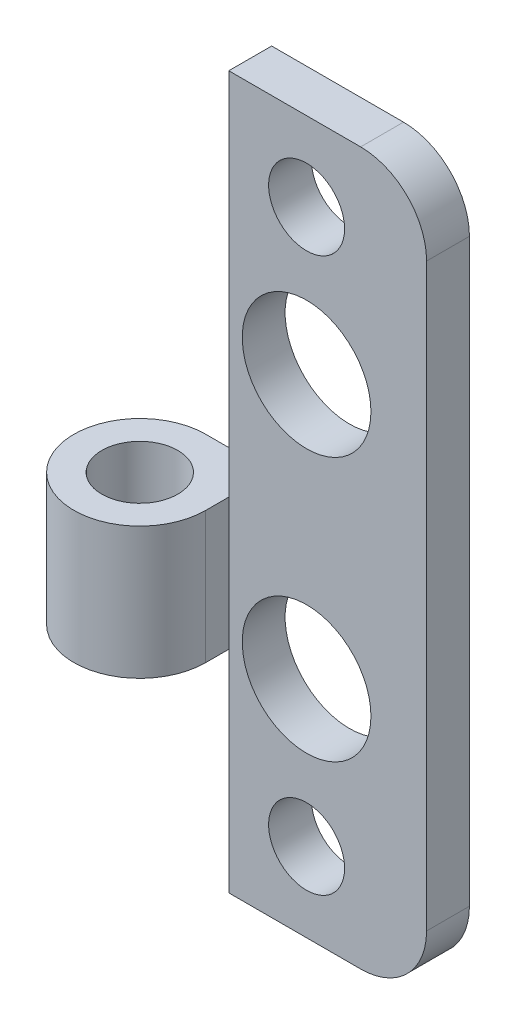
SolidWorks part; units mm, degrees
ref_plane "Front Plane" through (0, 0, 0) normal (0, 0, 1) x (1, 0, 0)
ref_plane "Top Plane" through (0, 0, 0) normal (0, 1, 0) x (1, 0, 0)
ref_plane "Right Plane" through (0, 0, 0) normal (1, 0, 0) x (0, 0, -1)
sketch "Sketch1" plane through (0, 0, 0) normal (0, 0, 1) x (1, 0, 0)
  line L0 (7.493, 46.99) -> (7.493, 54.61) construction
  line L1 (0, 0) -> (12.7, 0)
  line L2 (0, 0) -> (0, 68.58)
  line L3 (0, 68.58) -> (12.7, 68.58)
  line L4 (19.05, 6.35) -> (19.05, 62.23)
  line L5 (7.493, 46.99) -> (7.493, 21.59) construction
  line L6 (7.493, 34.29) -> (0, 34.29) construction
  circle A0 centre (7.493, 46.99) radius 3.6576 construction
  circle A1 centre (7.493, 21.59) radius 3.6576 construction
  circle A2 centre (7.493, 60.96) radius 3.6576
  circle A3 centre (7.493, 7.62) radius 3.6576
  arc A4 (12.7, 0) -> (19.05, 6.35) centre (12.7, 6.35) ccw
  arc A5 (19.05, 62.23) -> (12.7, 68.58) centre (12.7, 62.23) ccw
  circle A6 centre (7.493, 46.99) radius 6.1976 construction
  circle A7 centre (7.493, 21.59) radius 6.1976 construction
  circle A8 centre (7.493, 60.96) radius 6.1976 construction
  circle A9 centre (7.493, 7.62) radius 6.1976 construction
  point P16 (19.05, 0)
  dimension "D4" = 7.493
  dimension "D6" = 6.35
  dimension "D7" = 7.3152
  dimension "D9" = 7.62
  dimension "D1" = 19.05
  dimension "D2" = 68.58
  dimension "D3" = 7.62
  dimension "D5" = 25.4
  dimension "D8" = 7.62
extrude "Boss-Extrude1" add sketch "Sketch1" along normal blind 4.1275
sketch "Sketch2" plane through (0, 68.58, 0) normal (0, 1, 0) x (1, 0, 0)
  line L0 (0, 0) -> (-6.35, 0)
  line L2 (0, -6.35) -> (0, -4.1275)
  line L3 (0, -4.1275) -> (0, 0)
  circle A0 centre (-6.35, -6.35) radius 3.6576
  arc A2 (-6.35, 0) -> (0, -6.35) centre (-6.35, -6.35) ccw
  point P6 (-20.32, 0)
  dimension "D2" = 7.3152
  dimension "D1" = 6.35
extrude "Boss-Extrude2" add sketch "Sketch2" against normal blind 12.7 from offset 35.56 offset against normal yes
sketch "Sketch3" plane through (0, 0, 4.1275) normal (0, 0, 1) x (1, 0, 0)
  line L0 (0, 20.32) -> (0, 0) construction
  line L1 (7.493, 46.99) -> (7.493, 21.59) construction
  line L2 (7.493, 34.29) -> (19.05, 34.29) construction
  line L3 (19.05, 6.35) -> (19.05, 62.23) construction
  circle A0 centre (7.493, 46.99) radius 6.1976
  circle A1 centre (7.493, 21.59) radius 6.1976
  dimension "D1" = 12.3952
  dimension "D2" = 7.493
  dimension "D3" = 7.493
  dimension "D4" = 25.4
extrude "Cut-Extrude1" cut sketch "Sketch3" against normal through all
